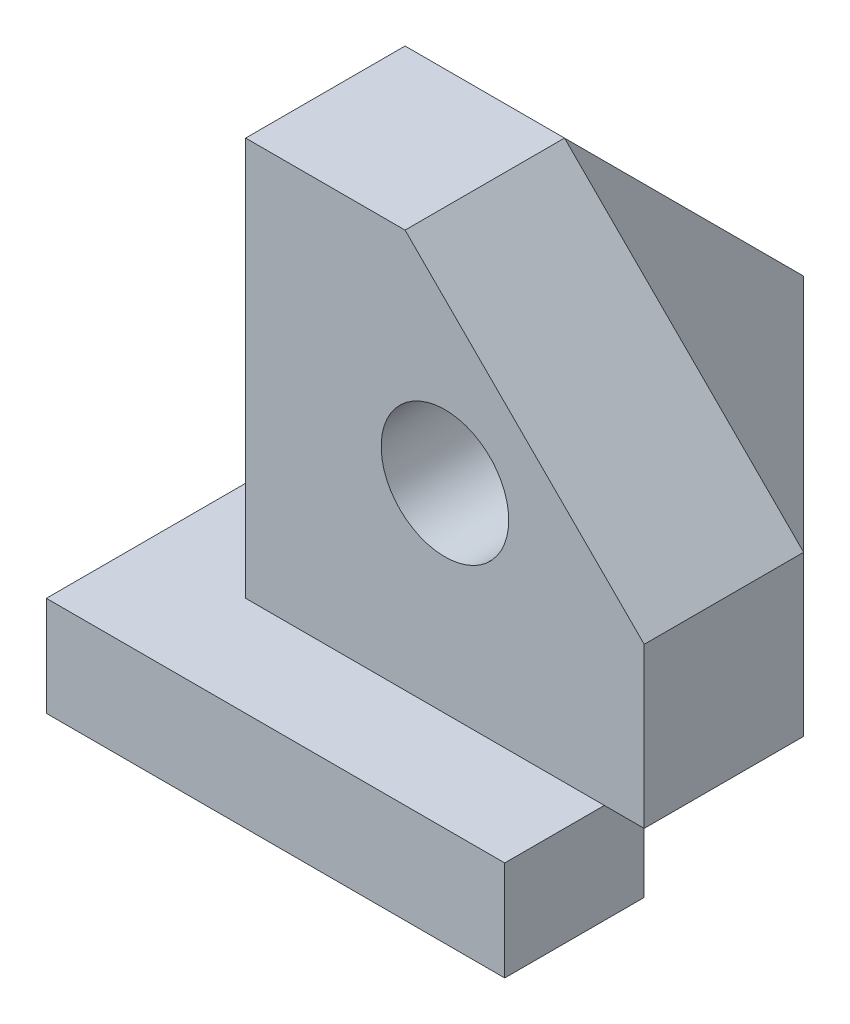
SolidWorks part; units mm, degrees
ref_plane "Front Plane" through (0, 0, 0) normal (0, 0, 1) x (1, 0, 0)
ref_plane "Top Plane" through (0, 0, 0) normal (0, 1, 0) x (1, 0, 0)
ref_plane "Right Plane" through (0, 0, 0) normal (1, 0, 0) x (0, 0, -1)
sketch "Sketch1" plane through (0, 0, 0) normal (0, 1, 0) x (1, 0, 0)
  line L1 (-5, -5) -> (5, -5)
  line L2 (-5, -5) -> (-5, 5)
  line L3 (-5, 5) -> (5, 5)
  line L4 (5, -5) -> (5, 5)
  line L5 (-5, -5) -> (5, 5) construction
  line L6 (-5, 5) -> (5, -5) construction
  point P0 (0, 0)
  dimension "D1" = 10
extrude "Boss-Extrude1" add sketch "Sketch1" along normal blind 10
sketch "Sketch2" plane through (0, 0, 5) normal (0, 0, 1) x (1, 0, 0)
  line L0 (-5, 10) -> (5, 0) construction
  circle A0 centre (0, 5) radius 1.6
  dimension "D1" = 3.2
extrude "Cut-Extrude1" cut sketch "Sketch2" against normal blind 3.2
sketch "Sketch3" plane through (0, 0, 0) normal (0, -1, 0) x (-1, 0, 0)
  line L0 (5, -5) -> (-5, 5) construction
  circle A0 centre (0, 0) radius 1.6
  dimension "D1" = 3.2
extrude "Cut-Extrude3" cut sketch "Sketch3" against normal blind 3.2
sketch "Sketch4" plane through (-5, 0, 0) normal (1, 0, 0) x (0, 0, -1)
  line L0 (5, 10) -> (-5, 0) construction
  circle A0 centre (0, 5) radius 1.6
  dimension "D1" = 3.2
extrude "Cut-Extrude4" cut sketch "Sketch4" along normal blind 3.2
chamfer "Chamfer1" distance 6 angle 45 3 edges at (5, 5, -5) (5, 10, 0) (0, 10, -5)
ref_plane "Plane1" through (0, -2.5, 0) normal (0, -1, 0) x (-1, 0, 0)
ref_plane "Plane2" through (0, 0, 7.5) normal (0, 0, 1) x (1, 0, 0)
ref_plane "Plane3" through (-7.5, 0, 0) normal (-1, 0, 0) x (0, 0, 1)
sketch "Sketch5" plane through (0, -2.5, 0) normal (0, -1, 0) x (-1, 0, 0)
  line L0 (-4, -4) -> (-4, -7.5)
  line L2 (-4, -7.5) -> (7.5, -7.5)
  line L3 (7.5, -7.5) -> (7.5, 4)
  line L4 (7.5, 4) -> (4, 4)
  line L5 (4, 0) -> (4, 4)
  line L6 (0, -4) -> (-4, -4)
  line L7 (0, 0) -> (0, -4) construction
  line L8 (0, 0) -> (4, 0) construction
  arc A0 (0, -4) -> (4, 0) centre (0, 0) ccw
  point P2 (0, 0)
  point P3 (0, 0)
  point P4 (3, 4)
  point P8 (0, 0)
  dimension "D1" = 7.5
  dimension "D3" = 4
  dimension "D2" = 11.5
extrude "Boss-Extrude2" add sketch "Sketch5" against normal blind 2.5
